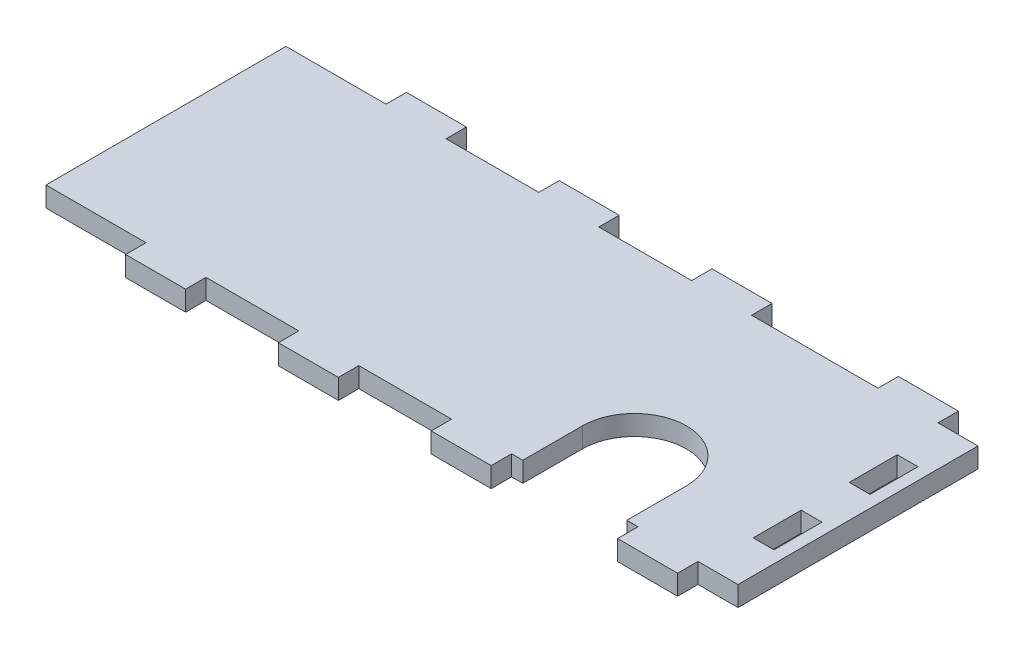
SolidWorks part; units mm, degrees
ref_plane "Front Plane" through (0, 0, 0) normal (0, 0, 1) x (1, 0, 0)
ref_plane "Top Plane" through (0, 0, 0) normal (0, 1, 0) x (1, 0, 0)
ref_plane "Right Plane" through (0, 0, 0) normal (1, 0, 0) x (0, 0, -1)
sketch "Sketch1" plane through (0, 0, 0) normal (0, 1, 0) x (1, 0, 0)
  line L0 (56.6, 26.4684) -> (56.6, -33.5316)
  line L1 (56.6, -33.5316) -> (46.6, -33.5316)
  line L2 (46.6, -33.5316) -> (46.6, -38.6316)
  line L3 (46.6, -38.6316) -> (31.6, -38.6316)
  line L4 (31.6, -38.6316) -> (31.6, -33.5316)
  line L6 (0, -33.5316) -> (0, -38.6316)
  line L7 (0, -38.6316) -> (-15, -38.6316)
  line L8 (-15, -38.6316) -> (-15, -33.5316)
  line L9 (-15, -33.5316) -> (-38.2, -33.5316)
  line L10 (-76.4, -33.5316) -> (-76.4, -38.6316)
  line L11 (-76.4, -38.6316) -> (-91.4, -38.6316)
  line L12 (-91.4, -38.6316) -> (-91.4, -33.5316)
  line L14 (-116.4, -33.5316) -> (-116.4, 26.4684)
  line L29 (-116.4, -33.5316) -> (-91.4, -33.5316)
  line L30 (31.6, -33.5316) -> (28.8, -33.5316)
  line L31 (28.8, -33.5316) -> (28.8, -18.6316)
  line L32 (-53.2, -33.5316) -> (-53.2, -38.6316)
  line L33 (-53.2, -38.6316) -> (-38.2, -38.6316)
  line L34 (2.8, -18.6316) -> (2.8, -33.5316)
  line L35 (2.8, -33.5316) -> (0, -33.5316)
  line L36 (-38.2, -38.6316) -> (-38.2, -33.5316)
  line L37 (-53.2, -33.5316) -> (-76.4, -33.5316)
  line L38 (0, 26.4684) -> (31.6, 26.4684)
  line L39 (56.6, 26.4684) -> (46.6, 26.4684)
  line L40 (46.6, 26.4684) -> (46.6, 31.5684)
  line L41 (46.6, 31.5684) -> (31.6, 31.5684)
  line L42 (31.6, 31.5684) -> (31.6, 26.4684)
  line L43 (0, 26.4684) -> (0, 31.5684)
  line L44 (0, 31.5684) -> (-15, 31.5684)
  line L45 (-15, 31.5684) -> (-15, 26.4684)
  line L46 (-15, 26.4684) -> (-38.2, 26.4684)
  line L47 (-38.2, 31.5684) -> (-38.2, 26.4684)
  line L48 (-53.2, 31.5684) -> (-38.2, 31.5684)
  line L49 (-53.2, 26.4684) -> (-53.2, 31.5684)
  line L50 (-53.2, 26.4684) -> (-76.4, 26.4684)
  line L51 (-76.4, 26.4684) -> (-76.4, 31.5684)
  line L52 (-76.4, 31.5684) -> (-91.4, 31.5684)
  line L53 (-91.4, 31.5684) -> (-91.4, 26.4684)
  line L54 (-116.4, 26.4684) -> (-91.4, 26.4684)
  line L57 (53.6, 14.4684) -> (48.4, 14.4684)
  line L58 (53.6, 14.4684) -> (53.6, 2.4684)
  line L59 (53.6, 2.4684) -> (48.4, 2.4684)
  line L60 (48.4, 14.4684) -> (48.4, 2.4684)
  line L61 (53.6, 14.4684) -> (48.4, 2.4684) construction
  line L62 (53.6, 2.4684) -> (48.4, 14.4684) construction
  line L64 (53.6, -21.5316) -> (48.4, -21.5316)
  line L65 (53.6, -21.5316) -> (53.6, -9.5316)
  line L66 (53.6, -9.5316) -> (48.4, -9.5316)
  line L67 (48.4, -21.5316) -> (48.4, -9.5316)
  line L68 (53.6, -21.5316) -> (48.4, -9.5316) construction
  line L69 (53.6, -9.5316) -> (48.4, -21.5316) construction
  arc A0 (28.8, -18.6316) -> (2.8, -18.6316) centre (15.8, -18.6316) ccw
  dimension "D43" = 14.9
  dimension "D1" = 60
  dimension "D2" = 10
  dimension "D3" = 15
  dimension "D4" = 31.6
  dimension "D5" = 15
  dimension "D6" = 61.4
  dimension "D7" = 15
  dimension "D8" = 25
  dimension "D9" = 5.1
  dimension "D10" = 5.1
  dimension "D11" = 5.1
  dimension "D12" = 5.1
  dimension "D13" = 5.1
  dimension "D14" = 5.1
  dimension "D15" = 12
  dimension "D16" = 12
  dimension "D17" = 5.2
  dimension "D18" = 10
  dimension "D19" = 5.1
  dimension "D20" = 15
  dimension "D21" = 2.8
  dimension "D22" = 14.9
  dimension "D23" = 13
  dimension "D24" = 5.1
  dimension "D25" = 15
  dimension "D26" = 23.2
  dimension "D27" = 5.1
  dimension "D28" = 31.6
  dimension "D29" = 5.1
  dimension "D30" = 15
  dimension "D31" = 5.1
  dimension "D32" = 23.2
  dimension "D33" = 5.1
  dimension "D34" = 15
  dimension "D35" = 5.1
  dimension "D36" = 23.2
  dimension "D37" = 5.1
  dimension "D38" = 15
  dimension "D39" = 5.1
  dimension "D40" = 25
  dimension "D41" = 60
  dimension "D42" = 12
  dimension "D44" = 2.8
  dimension "D46" = 12
  dimension "D47" = 5.2
extrude "Boss-Extrude1" add sketch "Sketch1" along normal blind 5
